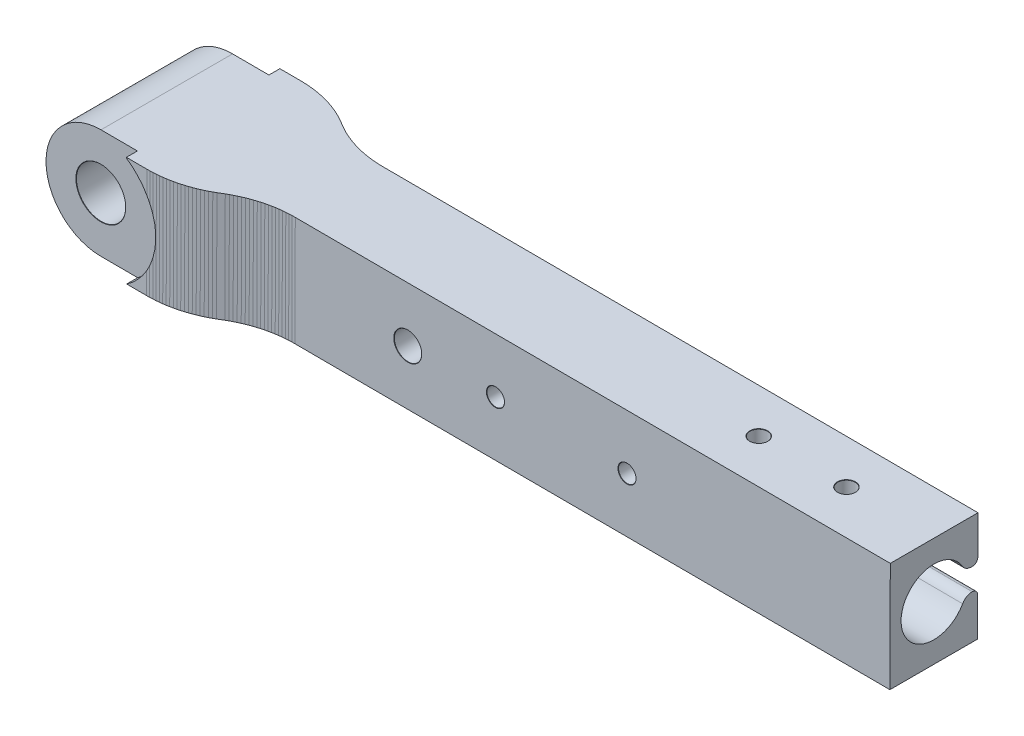
SolidWorks part; units mm, degrees
ref_plane "前视基准面" through (0, 0, 0) normal (0, 0, 1) x (1, 0, 0)
ref_plane "上视基准面" through (0, 0, 0) normal (0, 1, 0) x (1, 0, 0)
ref_plane "右视基准面" through (0, 0, 0) normal (1, 0, 0) x (0, 0, -1)
other "图形1"
sketch "草图1" plane through (-0.0177, -4.9477, 0) normal (-0.0036, -1, 0) x (1, -0.0036, 0)
  line L0 (0.0176, 6) -> (0.0176, -6)
  line L109 (14.3569, 4.096) -> (14.0827, 4.1382)
  line L110 (14.0827, 4.1382) -> (13.8098, 4.1879)
  line L111 (13.8098, 4.1879) -> (13.5384, 4.2452)
  line L112 (13.5384, 4.2452) -> (13.2687, 4.31)
  line L113 (13.2687, 4.31) -> (13.0008, 4.3823)
  line L114 (13.0008, 4.3823) -> (12.7351, 4.462)
  line L115 (12.7351, 4.462) -> (12.4717, 4.549)
  line L116 (12.4717, 4.549) -> (12.2108, 4.6432)
  line L117 (12.2108, 4.6432) -> (11.9527, 4.7447)
  line L118 (11.9527, 4.7447) -> (11.6974, 4.8533)
  line L119 (11.6974, 4.8533) -> (11.4453, 4.9689)
  line L120 (11.4453, 4.9689) -> (11.1964, 5.0915)
  line L121 (11.1964, 5.0915) -> (10.9511, 5.221)
  line L122 (10.9511, 5.221) -> (10.7094, 5.3572)
  line L123 (10.7094, 5.3572) -> (10.4716, 5.5)
  line L124 (10.4716, 5.5) -> (10.2339, 5.6428)
  line L125 (10.2339, 5.6428) -> (9.9922, 5.779)
  line L126 (9.9922, 5.779) -> (9.7468, 5.9085)
  line L127 (9.7468, 5.9085) -> (9.498, 6.0311)
  line L128 (9.498, 6.0311) -> (9.2459, 6.1467)
  line L129 (9.2459, 6.1467) -> (8.9906, 6.2553)
  line L130 (8.9906, 6.2553) -> (8.7324, 6.3568)
  line L131 (8.7324, 6.3568) -> (8.4716, 6.451)
  line L132 (8.4716, 6.451) -> (8.2082, 6.538)
  line L133 (8.2082, 6.538) -> (7.9424, 6.6177)
  line L134 (7.9424, 6.6177) -> (7.6746, 6.69)
  line L135 (7.6746, 6.69) -> (7.4049, 6.7548)
  line L136 (7.4049, 6.7548) -> (7.1335, 6.8121)
  line L137 (7.1335, 6.8121) -> (6.8606, 6.8618)
  line L138 (6.8606, 6.8618) -> (6.5864, 6.904)
  line L139 (6.5864, 6.904) -> (6.3112, 6.9385)
  line L140 (6.3112, 6.9385) -> (6.0351, 6.9654)
  line L141 (6.0351, 6.9654) -> (5.7584, 6.9846)
  line L142 (5.7584, 6.9846) -> (5.4812, 6.9962)
  line L143 (5.4812, 6.9962) -> (5.2038, 7)
  line L144 (5.2038, 7) -> (3.3345, 7)
  line L145 (3.3345, 7) -> (3.3345, 6)
  line L146 (3.3345, 6) -> (0.0179, 6)
  line L147 (0.0179, 6) -> (-0.1809, 6)
  line L148 (-0.1809, 6) -> (-0.3794, 6)
  line L149 (-0.3794, 6) -> (-0.5773, 6)
  line L150 (-0.5773, 6) -> (-0.7743, 6)
  line L151 (-0.7743, 6) -> (-0.9701, 6)
  line L152 (-0.9701, 6) -> (-1.1643, 6)
  line L153 (-1.1643, 6) -> (-1.3567, 6)
  line L154 (-1.3567, 6) -> (-1.547, 6)
  line L155 (-1.547, 6) -> (-1.7348, 6)
  line L156 (-1.7348, 6) -> (-1.7348, -6)
  line L157 (-1.7348, -6) -> (-1.547, -6)
  line L158 (-1.547, -6) -> (-1.3567, -6)
  line L159 (-1.3567, -6) -> (-1.1643, -6)
  line L160 (-1.1643, -6) -> (-0.9701, -6)
  line L161 (-0.9701, -6) -> (-0.7743, -6)
  line L162 (-0.7743, -6) -> (-0.5773, -6)
  line L163 (-0.5773, -6) -> (-0.3794, -6)
  line L164 (-0.3794, -6) -> (-0.1809, -6)
  line L165 (-0.1809, -6) -> (0.0179, -6)
  line L166 (0.0179, -6) -> (3.3345, -6)
  line L167 (3.3345, -6) -> (3.3345, -7)
  line L168 (3.3345, -7) -> (5.2038, -7)
  line L169 (5.2038, -7) -> (5.4812, -6.9962)
  line L170 (5.4812, -6.9962) -> (5.7584, -6.9846)
  line L171 (5.7584, -6.9846) -> (6.0351, -6.9654)
  line L172 (6.0351, -6.9654) -> (6.3112, -6.9385)
  line L173 (6.3112, -6.9385) -> (6.5864, -6.904)
  line L174 (6.5864, -6.904) -> (6.8606, -6.8618)
  line L175 (6.8606, -6.8618) -> (7.1335, -6.8121)
  line L176 (7.1335, -6.8121) -> (7.4049, -6.7548)
  line L177 (7.4049, -6.7548) -> (7.6746, -6.69)
  line L178 (7.6746, -6.69) -> (7.9424, -6.6177)
  line L179 (7.9424, -6.6177) -> (8.2082, -6.538)
  line L180 (8.2082, -6.538) -> (8.4716, -6.451)
  line L181 (8.4716, -6.451) -> (8.7324, -6.3568)
  line L182 (8.7324, -6.3568) -> (8.9906, -6.2553)
  line L183 (8.9906, -6.2553) -> (9.2459, -6.1467)
  line L184 (9.2459, -6.1467) -> (9.498, -6.0311)
  line L185 (9.498, -6.0311) -> (9.7468, -5.9085)
  line L186 (9.7468, -5.9085) -> (9.9922, -5.779)
  line L187 (9.9922, -5.779) -> (10.2339, -5.6428)
  line L188 (10.2339, -5.6428) -> (10.4716, -5.5)
  line L189 (10.4716, -5.5) -> (10.7094, -5.3572)
  line L190 (10.7094, -5.3572) -> (10.9511, -5.221)
  line L191 (10.9511, -5.221) -> (11.1964, -5.0915)
  line L192 (11.1964, -5.0915) -> (11.4453, -4.9689)
  line L193 (11.4453, -4.9689) -> (11.6974, -4.8533)
  line L194 (11.6974, -4.8533) -> (11.9527, -4.7447)
  line L195 (11.9527, -4.7447) -> (12.2108, -4.6432)
  line L196 (12.2108, -4.6432) -> (12.4717, -4.549)
  line L197 (12.4717, -4.549) -> (12.7351, -4.462)
  line L198 (12.7351, -4.462) -> (13.0008, -4.3823)
  line L199 (13.0008, -4.3823) -> (13.2687, -4.31)
  line L200 (13.2687, -4.31) -> (13.5384, -4.2452)
  line L201 (13.5384, -4.2452) -> (13.8098, -4.1879)
  line L202 (13.8098, -4.1879) -> (14.0827, -4.1382)
  line L203 (14.0827, -4.1382) -> (14.3569, -4.096)
  line L204 (14.3569, -4.096) -> (14.6321, -4.0615)
  line L205 (14.6321, -4.0615) -> (14.9082, -4.0346)
  line L206 (14.9082, -4.0346) -> (15.1849, -4.0154)
  line L207 (15.1849, -4.0154) -> (15.4621, -4.0038)
  line L208 (15.4621, -4.0038) -> (15.7394, -4)
  line L209 (15.7394, -4) -> (50.0176, -4)
  line L210 (50.0176, -4) -> (50.0176, 4)
  line L211 (50.0176, 4) -> (15.7394, 4)
  line L212 (15.7394, 4) -> (15.4621, 4.0038)
  line L213 (15.4621, 4.0038) -> (15.1849, 4.0154)
  line L214 (15.1849, 4.0154) -> (14.9082, 4.0346)
  line L215 (14.9082, 4.0346) -> (14.6321, 4.0615)
  line L216 (14.6321, 4.0615) -> (14.3569, 4.096)
  line L217 (14.3569, 4.096) -> (14.0827, 4.1382)
  line L218 (14.0827, 4.1382) -> (13.8098, 4.1879)
  line L219 (13.8098, 4.1879) -> (13.5384, 4.2452)
  line L220 (13.5384, 4.2452) -> (13.2687, 4.31)
  line L221 (13.2687, 4.31) -> (13.0008, 4.3823)
  line L222 (13.0008, 4.3823) -> (12.7351, 4.462)
  line L223 (12.7351, 4.462) -> (12.4717, 4.549)
  line L224 (12.4717, 4.549) -> (12.2108, 4.6432)
  line L225 (12.2108, 4.6432) -> (11.9527, 4.7447)
  line L226 (11.9527, 4.7447) -> (11.6974, 4.8533)
  line L227 (11.6974, 4.8533) -> (11.4453, 4.9689)
  line L228 (11.4453, 4.9689) -> (11.1964, 5.0915)
  line L229 (11.1964, 5.0915) -> (10.9511, 5.221)
  line L230 (10.9511, 5.221) -> (10.7094, 5.3572)
  line L231 (10.7094, 5.3572) -> (10.4716, 5.5)
  line L232 (10.4716, 5.5) -> (10.2339, 5.6428)
  line L233 (10.2339, 5.6428) -> (9.9922, 5.779)
  line L234 (9.9922, 5.779) -> (9.7468, 5.9085)
  line L235 (9.7468, 5.9085) -> (9.498, 6.0311)
  line L236 (9.498, 6.0311) -> (9.2459, 6.1467)
  line L237 (9.2459, 6.1467) -> (8.9906, 6.2553)
  line L238 (8.9906, 6.2553) -> (8.7324, 6.3568)
  line L239 (8.7324, 6.3568) -> (8.4716, 6.451)
  line L240 (8.4716, 6.451) -> (8.2082, 6.538)
  line L241 (8.2082, 6.538) -> (7.9424, 6.6177)
  line L242 (7.9424, 6.6177) -> (7.6746, 6.69)
  line L243 (7.6746, 6.69) -> (7.4049, 6.7548)
  line L244 (7.4049, 6.7548) -> (7.1335, 6.8121)
  line L245 (7.1335, 6.8121) -> (6.8606, 6.8618)
  line L246 (6.8606, 6.8618) -> (6.5864, 6.904)
  line L247 (6.5864, 6.904) -> (6.3112, 6.9385)
  line L248 (6.3112, 6.9385) -> (6.0351, 6.9654)
  line L249 (6.0351, 6.9654) -> (5.7584, 6.9846)
  line L250 (5.7584, 6.9846) -> (5.4812, 6.9962)
  line L251 (5.4812, 6.9962) -> (5.2038, 7)
  line L252 (5.2038, 7) -> (3.3345, 7)
  line L253 (3.3345, 7) -> (3.3345, 6)
  line L254 (3.3345, 6) -> (0.0179, 6)
  line L255 (0.0179, 6) -> (-0.1809, 6)
  line L256 (-0.1809, 6) -> (-0.3794, 6)
  line L257 (-0.3794, 6) -> (-0.5773, 6)
  line L258 (-0.5773, 6) -> (-0.7743, 6)
  line L259 (-0.7743, 6) -> (-0.9701, 6)
  line L260 (-0.9701, 6) -> (-1.1643, 6)
  line L261 (-1.1643, 6) -> (-1.3567, 6)
  line L262 (-1.3567, 6) -> (-1.547, 6)
  line L263 (-1.547, 6) -> (-1.7348, 6)
  line L264 (-1.7348, 6) -> (-1.7348, -6)
  line L265 (-1.7348, -6) -> (-1.547, -6)
  line L266 (-1.547, -6) -> (-1.3567, -6)
  line L267 (-1.3567, -6) -> (-1.1643, -6)
  line L268 (-1.1643, -6) -> (-0.9701, -6)
  line L269 (-0.9701, -6) -> (-0.7743, -6)
  line L270 (-0.7743, -6) -> (-0.5773, -6)
  line L271 (-0.5773, -6) -> (-0.3794, -6)
  line L272 (-0.3794, -6) -> (-0.1809, -6)
  line L273 (-0.1809, -6) -> (0.0179, -6)
  line L274 (0.0179, -6) -> (3.3345, -6)
  line L275 (3.3345, -6) -> (3.3345, -7)
  line L276 (3.3345, -7) -> (5.2038, -7)
  line L277 (5.2038, -7) -> (5.4812, -6.9962)
  line L278 (5.4812, -6.9962) -> (5.7584, -6.9846)
  line L279 (5.7584, -6.9846) -> (6.0351, -6.9654)
  line L280 (6.0351, -6.9654) -> (6.3112, -6.9385)
  line L281 (6.3112, -6.9385) -> (6.5864, -6.904)
  line L282 (6.5864, -6.904) -> (6.8606, -6.8618)
  line L283 (6.8606, -6.8618) -> (7.1335, -6.8121)
  line L284 (7.1335, -6.8121) -> (7.4049, -6.7548)
  line L285 (7.4049, -6.7548) -> (7.6746, -6.69)
  line L286 (7.6746, -6.69) -> (7.9424, -6.6177)
  line L287 (7.9424, -6.6177) -> (8.2082, -6.538)
  line L288 (8.2082, -6.538) -> (8.4716, -6.451)
  line L289 (8.4716, -6.451) -> (8.7324, -6.3568)
  line L290 (8.7324, -6.3568) -> (8.9906, -6.2553)
  line L291 (8.9906, -6.2553) -> (9.2459, -6.1467)
  line L292 (9.2459, -6.1467) -> (9.498, -6.0311)
  line L293 (9.498, -6.0311) -> (9.7468, -5.9085)
  line L294 (9.7468, -5.9085) -> (9.9922, -5.779)
  line L295 (9.9922, -5.779) -> (10.2339, -5.6428)
  line L296 (10.2339, -5.6428) -> (10.4716, -5.5)
  line L297 (10.4716, -5.5) -> (10.7094, -5.3572)
  line L298 (10.7094, -5.3572) -> (10.9511, -5.221)
  line L299 (10.9511, -5.221) -> (11.1964, -5.0915)
  line L300 (11.1964, -5.0915) -> (11.4453, -4.9689)
  line L301 (11.4453, -4.9689) -> (11.6974, -4.8533)
  line L302 (11.6974, -4.8533) -> (11.9527, -4.7447)
  line L303 (11.9527, -4.7447) -> (12.2108, -4.6432)
  line L304 (12.2108, -4.6432) -> (12.4717, -4.549)
  line L305 (12.4717, -4.549) -> (12.7351, -4.462)
  line L306 (12.7351, -4.462) -> (13.0008, -4.3823)
  line L307 (13.0008, -4.3823) -> (13.2687, -4.31)
  line L308 (13.2687, -4.31) -> (13.5384, -4.2452)
  line L309 (13.5384, -4.2452) -> (13.8098, -4.1879)
  line L310 (13.8098, -4.1879) -> (14.0827, -4.1382)
  line L311 (14.0827, -4.1382) -> (14.3569, -4.096)
  line L312 (14.3569, -4.096) -> (14.6321, -4.0615)
  line L313 (14.6321, -4.0615) -> (14.9082, -4.0346)
  line L314 (14.9082, -4.0346) -> (15.1849, -4.0154)
  line L315 (15.1849, -4.0154) -> (15.4621, -4.0038)
  line L316 (15.4621, -4.0038) -> (15.7394, -4)
  line L317 (15.7394, -4) -> (50.0176, -4)
  line L318 (50.0176, -4) -> (50.0176, 4)
  line L319 (50.0176, 4) -> (15.7394, 4)
  line L320 (15.7394, 4) -> (15.4621, 4.0038)
  line L321 (15.4621, 4.0038) -> (15.1849, 4.0154)
  line L322 (15.1849, 4.0154) -> (14.9082, 4.0346)
  line L323 (14.9082, 4.0346) -> (14.6321, 4.0615)
  line L324 (14.6321, 4.0615) -> (14.3569, 4.096)
  dimension "D2" = 50
  dimension "D1" = 0
extrude "凸台-拉伸2" add sketch "草图1" against normal blind 10 contours L323 L324 L217 L218 L219 L220 L221 L222 L223 L224 L225 L226 L227 L228 L229 L230 L231 L232 L233 L234 L235 L236 L237 L238 L239 L240 L241 L242 L243 L244 L245 L246 L247 L248 L249 L250 L251 L252 L253 L254 L255 L0 L273 L274 L275 L276 L277 L278 L279 L280 L281
sketch "草图2" plane through (0.0176, -0.0001, 0) normal (-1, 0.0036, 0) x (0, 0, 1)
  line L0 (6, 0.0523) -> (-6, 0.0523)
  line L1 (6, 5.0523) -> (6, -4.9477) construction
  line L2 (-6, 5.0523) -> (-6, -4.9477) construction
  line L3 (6, 0.0523) -> (6, 5.0523)
  line L4 (6, 5.0523) -> (-6, 5.0523)
  line L5 (-6, 5.0523) -> (-6, 0.0523)
revolve "旋转1" add sketch "草图2" angle 180 about L0
sketch "草图3" plane through (0, 0, 6) normal (0, 0, 1) x (1, 0, 0)
  line L0 (0.0356, 5.0522) -> (-0.0001, -4.9477) construction
hole_wizard "M4 间隙孔1" positions "草图8" profile "草图7" hole size "M4" standard "GB" end condition through all
sketch "草图8" plane through (0, 0, 6) normal (0, 0, 1) x (1, 0, 0)
  line L0 (0.0356, 5.0522) -> (-0.0001, -4.9477) construction
  point P0 (0.0177, 0.0522)
sketch "草图7" plane through (0.0177, 0.0522, 6) normal (1, 0, 0) x (0, -1, 0)
  line L0 (0, 0) -> (0, 13)
  line L1 (0, 13) -> (2.25, 13)
  line L2 (2.25, 13) -> (2.25, 0.025)
  line L3 (2.25, 0.025) -> (2.275, 0)
  line L5 (2.275, 0) -> (0, 0)
  line L6 (-2.25, 0.025) -> (-2.275, 0) construction
  line L11 (0, -6.35) -> (0, 107.95) construction
  dimension "通孔孔直径" = 4.5
  dimension "通孔孔深度" = 13
  dimension "近端锥形沉头孔直径" = 4.55
  dimension "近端锥形沉头孔角度" = 90
sketch "草图9" plane through (50.0172, -0.1788, 0) normal (1, -0.0036, 0) x (0, 0, -1)
  line L0 (-4.0346, 0.0523) -> (4.0038, 0.0523) construction
  line L1 (-4.0346, 5.0523) -> (-4.0346, -4.9477) construction
  line L2 (4.0038, 5.0523) -> (4.0038, -4.9477) construction
  line L3 (0, 5.0523) -> (0, -4.9477) construction
  line L4 (4, 5.0523) -> (-4, 5.0523) construction
  line L5 (4, -4.9477) -> (-4, -4.9477) construction
  circle A0 centre (-0.0154, 0.0523) radius 2.25
  dimension "D1" = 4.5
extrude "切除-拉伸1" cut sketch "草图9" against normal blind 20
sketch "草图12" plane through (0, 0, 4) normal (0, 0, 1) x (1, 0, 0)
  line L0 (50.0174, -0.1265) -> (15.7395, -0.004) construction
  line L1 (50.0353, 4.8734) -> (49.9995, -5.1265) construction
  line L2 (15.7574, 4.996) -> (15.7216, -5.004) construction
hole_wizard "M2 螺纹孔的螺纹孔钻头1" positions "草图13" profile "草图14" hole size "M2" standard "GB" end condition through all
sketch "草图13" plane through (0, 0, 4) normal (0, 0, 1) x (1, 0, 0)
  line L0 (50.0174, -0.1265) -> (15.7395, -0.004) construction
  line L1 (50.0353, 4.8734) -> (49.9995, -5.1265) construction
  point P0 (46.0175, -0.1122)
  point P4 (34.0175, -0.0693)
  dimension "D1" = 4
  dimension "D2" = 16
sketch "草图14" plane through (46.0175, -0.1122, 4) normal (1, 0, 0) x (0, -1, 0)
  line L0 (0, 0) -> (0, 11)
  line L1 (0, 11) -> (0.8, 11)
  line L2 (0.8, 11) -> (0.8, 0.025)
  line L3 (0.8, 0.025) -> (0.825, 0)
  line L5 (0.825, 0) -> (0, 0)
  line L6 (-0.8, 0.025) -> (-0.825, 0) construction
  line L11 (0, -6.35) -> (0, 107.95) construction
  dimension "通孔孔直径" = 1.6
  dimension "通孔孔深度" = 11
  dimension "近端锥形沉头孔直径" = 1.65
  dimension "近端锥形沉头孔角度" = 90
hole_wizard "M3 螺纹孔的螺纹孔钻头1" positions "草图15" profile "草图16" hole size "M3" standard "GB" end condition through all
sketch "草图15" plane through (0, 0, 4) normal (0, 0, 1) x (1, 0, 0)
  line L0 (50.0174, -0.1265) -> (15.7395, -0.004) construction
  line L1 (50.0353, 4.8734) -> (49.9995, -5.1265) construction
  point P0 (26.0176, -0.0407)
  dimension "D1" = 24
sketch "草图16" plane through (26.0176, -0.0407, 4) normal (1, 0, 0) x (0, -1, 0)
  line L0 (0, 0) -> (0, 11)
  line L1 (0, 11) -> (1.25, 11)
  line L2 (1.25, 11) -> (1.25, 0.025)
  line L3 (1.25, 0.025) -> (1.275, 0)
  line L5 (1.275, 0) -> (0, 0)
  line L6 (-1.25, 0.025) -> (-1.275, 0) construction
  line L11 (0, -6.35) -> (0, 107.95) construction
  dimension "通孔孔直径" = 2.5
  dimension "通孔孔深度" = 11
  dimension "近端锥形沉头孔直径" = 2.55
  dimension "近端锥形沉头孔角度" = 90
sketch "草图17" plane through (0, 0, 6) normal (0, 0, 1) x (1, 0, 0)
  circle A0 centre (0, 0) radius 6
  dimension "D1" = 12
extrude "切除-拉伸2" cut sketch "草图17" along normal through all
sketch "草图18" plane through (0, 0, -6) normal (0, 0, -1) x (-1, 0, 0)
  circle A1 centre (0, 0) radius 6
  circle A2 centre (0, 0) radius 6
  dimension "D1" = 0
extrude "切除-拉伸3" cut sketch "草图18" along normal through all
sketch "草图19" plane through (50.0172, -0.1788, 0) normal (1, -0.0036, 0) x (0, 0, -1)
  line L1 (-4, 5.0523) -> (4, 5.0523)
  line L2 (-4, 5.0523) -> (-4, -4.9477)
  line L3 (-4, -4.9477) -> (4, -4.9477)
  line L4 (4, 5.0523) -> (4, -4.9477)
extrude "凸台-拉伸3" add sketch "草图19" along normal blind 20
sketch "草图20" plane through (70.0171, -0.2504, 0) normal (1, -0.0036, 0) x (0, 0, -1)
  line L0 (0, 0.0523) -> (4.0038, 0.0523) construction
  line L1 (4.0038, 5.0523) -> (4.0038, -4.9477) construction
  line L2 (4, -4.9477) -> (4, 5.0523) construction
  line L3 (0, 1.0523) -> (4, 1.0523)
  line L4 (0, 1.0523) -> (0, -0.9477)
  line L5 (0, -0.9477) -> (4, -0.9477)
  line L6 (4, 1.0523) -> (4, -0.9477)
  circle A0 centre (0, 0) radius 3
  line M4 (4, -4.9477) -> (4, 5.0523)
  dimension "D1" = 6
  dimension "D2" = 2
extrude "切除-拉伸5" cut sketch "草图20" against normal blind 20 contours L3 A0 L5 L4 | L4 L0 A0 L3 | L0 L4 L5 A0 | A0 L0 L6 L3 | L0 A0 L5 M4
hole_wizard "M2 螺纹孔的螺纹孔钻头2" positions "草图21" profile "草图22" hole size "M2" standard "GB" end condition through all
sketch "草图21" plane through (0.0181, 5.0523, 0) normal (0.0036, 1, 0) x (1, -0.0036, 0)
  line L0 (0, 0) -> (70.0176, 0) construction
  line L1 (70.0176, 4) -> (70.0176, -4) construction
  point P0 (54.0176, 0)
  point P2 (62.0176, 0)
  dimension "D1" = 8
  dimension "D2" = 8
sketch "草图22" plane through (54.0353, 4.8591, 0) normal (0, 0, 1) x (-1, 0.0036, 0)
  line L0 (0, 0) -> (0, 10.2681)
  line L1 (0, 10.2681) -> (0.8, 10.2681)
  line L2 (0.8, 10.2681) -> (0.8, 0.025)
  line L3 (0.8, 0.025) -> (0.825, 0)
  line L5 (0.825, 0) -> (0, 0)
  line L6 (-0.8, 0.025) -> (-0.825, 0) construction
  line L11 (0, -6.35) -> (0, 107.95) construction
  dimension "通孔孔直径" = 1.6
  dimension "通孔孔深度" = 10.2681
  dimension "近端锥形沉头孔直径" = 1.65
  dimension "近端锥形沉头孔角度" = 90
fillet "圆角1" radius 0.5 3 edges at (60.0138, -1.1623, -4) (50.0174, -0.1265, -4) (60.0209, 0.8377, -4)
fillet "圆角2" radius 1 2 edges at (60.0138, -1.1623, -2.8464) (60.0209, 0.8377, -2.8094)
fillet "圆角3" radius 0.5 1 edges at (50.0255, 2.1234, 0.0154)
